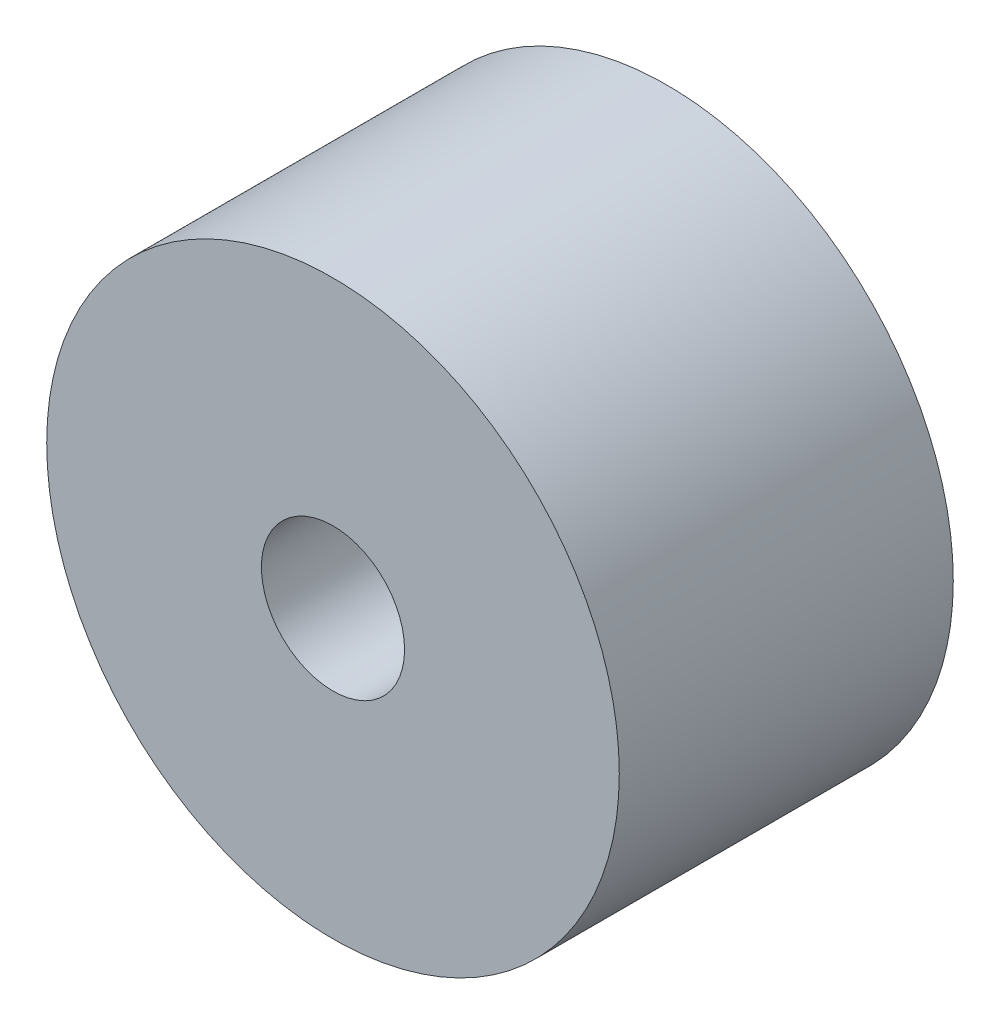
SolidWorks part; units mm, degrees
ref_plane "Plan de face" through (0, 0, 0) normal (0, 0, 1) x (1, 0, 0)
ref_plane "Plan de dessus" through (0, 0, 0) normal (0, 1, 0) x (1, 0, 0)
ref_plane "Plan de droite" through (0, 0, 0) normal (1, 0, 0) x (0, 0, -1)
sketch "Esquisse1" plane through (0, 0, 0) normal (0, 0, 1) x (1, 0, 0)
  arc A0 (2.9773, 0.3683) -> (2.9271, 0.6573) centre (0, 0) ccw
  arc A1 (2.1922, 2.048) -> (1.9817, 2.2523) centre (0, 0) ccw
  arc A2 (0.5698, 2.9454) -> (0.2794, 2.987) centre (0, 0) ccw
  arc A3 (-1.2703, 2.7178) -> (-1.5297, 2.5807) centre (0, 0) ccw
  arc A4 (-2.6252, 1.4521) -> (-2.7544, 1.1887) centre (0, 0) ccw
  arc A5 (-2.9773, -0.3683) -> (-2.9271, -0.6573) centre (0, 0) ccw
  arc A6 (-2.1922, -2.048) -> (-1.9817, -2.2523) centre (0, 0) ccw
  arc A7 (-0.5698, -2.9454) -> (-0.2794, -2.987) centre (0, 0) ccw
  arc A8 (1.2703, -2.7178) -> (1.5297, -2.5807) centre (0, 0) ccw
  arc A9 (2.6252, -1.4521) -> (2.7544, -1.1887) centre (0, 0) ccw
  arc A10 (1.8368, -0.3764) -> (1.8687, -0.154) centre (0, 0) ccw
  arc A11 (1.7073, 0.7751) -> (1.6023, 0.9738) centre (0, 0) ccw
  arc A12 (0.9256, 1.6306) -> (0.7239, 1.7296) centre (0, 0) ccw
  arc A13 (-0.2096, 1.8632) -> (-0.431, 1.8248) centre (0, 0) ccw
  arc A14 (-1.2648, 1.3842) -> (-1.4213, 1.2229) centre (0, 0) ccw
  arc A15 (-1.8368, 0.3764) -> (-1.8687, 0.154) centre (0, 0) ccw
  arc A16 (-1.7073, -0.7751) -> (-1.6023, -0.9738) centre (0, 0) ccw
  arc A17 (-0.9256, -1.6306) -> (-0.7239, -1.7296) centre (0, 0) ccw
  arc A18 (0.2096, -1.8632) -> (0.431, -1.8248) centre (0, 0) ccw
  arc A19 (1.2648, -1.3842) -> (1.4213, -1.2229) centre (0, 0) ccw
  circle A20 centre (0, 0) radius 0.75
  spline S0 degree 3 poles (2.349, 0) (2.3611, 0) (2.4126, 0.0085) (2.4945, 0.0326) (2.6584, 0.1065) (2.823, 0.2207) (2.9394, 0.3292) (2.9773, 0.3683) knots 0 0 0 0 0.036251 0.155621 0.255291 0.575255 0.744085 0.744085 0.744085 0.744085
  spline S1 degree 3 poles (2.2114, 0.7921) (2.2228, 0.7962) (2.2741, 0.8056) (2.3594, 0.8105) (2.5386, 0.7962) (2.7321, 0.7442) (2.8782, 0.6813) (2.9271, 0.6573) knots 0 0 0 0 0.036251 0.155621 0.255291 0.575255 0.744085 0.744085 0.744085 0.744085
  spline S2 degree 3 poles (1.9004, 1.3807) (1.9102, 1.3878) (1.9469, 1.4249) (1.9989, 1.4926) (2.0881, 1.6487) (2.1541, 1.8379) (2.1845, 1.9941) (2.1922, 2.048) knots 0 0 0 0 0.036251 0.155621 0.255291 0.575255 0.744085 0.744085 0.744085 0.744085
  spline S3 degree 3 poles (1.3235, 1.9407) (1.3303, 1.9507) (1.3663, 1.9885) (1.4324, 2.0425) (1.5858, 2.1363) (1.7728, 2.2079) (1.9281, 2.243) (1.9817, 2.2523) knots 0 0 0 0 0.036251 0.155621 0.255291 0.575255 0.744085 0.744085 0.744085 0.744085
  spline S4 degree 3 poles (0.7259, 2.234) (0.7296, 2.2455) (0.7375, 2.2971) (0.7398, 2.3825) (0.7202, 2.5612) (0.6625, 2.753) (0.5952, 2.8973) (0.5698, 2.9454) knots 0 0 0 0 0.036251 0.155621 0.255291 0.575255 0.744085 0.744085 0.744085 0.744085
  spline S5 degree 3 poles (-0.07, 2.348) (-0.0704, 2.36) (-0.0634, 2.4118) (-0.0417, 2.4943) (0.0272, 2.6604) (0.1365, 2.8283) (0.2415, 2.9479) (0.2794, 2.987) knots 0 0 0 0 0.036251 0.155621 0.255291 0.575255 0.744085 0.744085 0.744085 0.744085
  spline S6 degree 3 poles (-0.7259, 2.234) (-0.7296, 2.2455) (-0.7536, 2.2919) (-0.8019, 2.3623) (-0.9228, 2.4954) (-1.0823, 2.6166) (-1.2215, 2.6938) (-1.2703, 2.7178) knots 0 0 0 0 0.036251 0.155621 0.255291 0.575255 0.744085 0.744085 0.744085 0.744085
  spline S7 degree 3 poles (-1.4367, 1.8584) (-1.4441, 1.8679) (-1.4689, 1.9139) (-1.4999, 1.9934) (-1.5417, 2.1683) (-1.552, 2.3684) (-1.5374, 2.5268) (-1.5297, 2.5807) knots 0 0 0 0 0.036251 0.155621 0.255291 0.575255 0.744085 0.744085 0.744085 0.744085
  spline S8 degree 3 poles (-1.9004, 1.3807) (-1.9102, 1.3878) (-1.9568, 1.4112) (-2.0373, 1.4398) (-2.2133, 1.4764) (-2.4136, 1.4808) (-2.5715, 1.4614) (-2.6252, 1.4521) knots 0 0 0 0 0.036251 0.155621 0.255291 0.575255 0.744085 0.744085 0.744085 0.744085
  spline S9 degree 3 poles (-2.2547, 0.659) (-2.2663, 0.6624) (-2.3133, 0.6849) (-2.3852, 0.7311) (-2.5218, 0.848) (-2.6477, 1.0038) (-2.729, 1.1406) (-2.7544, 1.1887) knots 0 0 0 0 0.036251 0.155621 0.255291 0.575255 0.744085 0.744085 0.744085 0.744085
  spline S10 degree 3 poles (-2.349, 0) (-2.3611, 0) (-2.4126, -0.0085) (-2.4945, -0.0326) (-2.6584, -0.1065) (-2.823, -0.2207) (-2.9394, -0.3292) (-2.9773, -0.3683) knots 0 0 0 0 0.036251 0.155621 0.255291 0.575255 0.744085 0.744085 0.744085 0.744085
  spline S11 degree 3 poles (-2.2114, -0.7921) (-2.2228, -0.7962) (-2.2741, -0.8056) (-2.3594, -0.8105) (-2.5386, -0.7962) (-2.7321, -0.7442) (-2.8782, -0.6813) (-2.9271, -0.6573) knots 0 0 0 0 0.036251 0.155621 0.255291 0.575255 0.744085 0.744085 0.744085 0.744085
  spline S12 degree 3 poles (-1.9004, -1.3807) (-1.9102, -1.3878) (-1.9469, -1.4249) (-1.9989, -1.4926) (-2.0881, -1.6487) (-2.1541, -1.8379) (-2.1845, -1.9941) (-2.1922, -2.048) knots 0 0 0 0 0.036251 0.155621 0.255291 0.575255 0.744085 0.744085 0.744085 0.744085
  spline S13 degree 3 poles (-1.3235, -1.9407) (-1.3303, -1.9507) (-1.3663, -1.9885) (-1.4324, -2.0425) (-1.5858, -2.1363) (-1.7728, -2.2079) (-1.9281, -2.243) (-1.9817, -2.2523) knots 0 0 0 0 0.036251 0.155621 0.255291 0.575255 0.744085 0.744085 0.744085 0.744085
  spline S14 degree 3 poles (-0.7259, -2.234) (-0.7296, -2.2455) (-0.7375, -2.2971) (-0.7398, -2.3825) (-0.7202, -2.5612) (-0.6625, -2.753) (-0.5952, -2.8973) (-0.5698, -2.9454) knots 0 0 0 0 0.036251 0.155621 0.255291 0.575255 0.744085 0.744085 0.744085 0.744085
  spline S15 degree 3 poles (0.07, -2.348) (0.0704, -2.36) (0.0634, -2.4118) (0.0417, -2.4943) (-0.0272, -2.6604) (-0.1365, -2.8283) (-0.2415, -2.9479) (-0.2794, -2.987) knots 0 0 0 0 0.036251 0.155621 0.255291 0.575255 0.744085 0.744085 0.744085 0.744085
  spline S16 degree 3 poles (0.7259, -2.234) (0.7296, -2.2455) (0.7536, -2.2919) (0.8019, -2.3623) (0.9228, -2.4954) (1.0823, -2.6166) (1.2215, -2.6938) (1.2703, -2.7178) knots 0 0 0 0 0.036251 0.155621 0.255291 0.575255 0.744085 0.744085 0.744085 0.744085
  spline S17 degree 3 poles (1.4367, -1.8584) (1.4441, -1.8679) (1.4689, -1.9139) (1.4999, -1.9934) (1.5417, -2.1683) (1.552, -2.3684) (1.5374, -2.5268) (1.5297, -2.5807) knots 0 0 0 0 0.036251 0.155621 0.255291 0.575255 0.744085 0.744085 0.744085 0.744085
  spline S18 degree 3 poles (1.9004, -1.3807) (1.9102, -1.3878) (1.9568, -1.4112) (2.0373, -1.4398) (2.2133, -1.4764) (2.4136, -1.4808) (2.5715, -1.4614) (2.6252, -1.4521) knots 0 0 0 0 0.036251 0.155621 0.255291 0.575255 0.744085 0.744085 0.744085 0.744085
  spline S19 degree 3 poles (2.2547, -0.659) (2.2663, -0.6624) (2.3133, -0.6849) (2.3852, -0.7311) (2.5218, -0.848) (2.6477, -1.0038) (2.729, -1.1406) (2.7544, -1.1887) knots 0 0 0 0 0.036251 0.155621 0.255291 0.575255 0.744085 0.744085 0.744085 0.744085
  spline S20 degree 3 poles (2.349, 0) (2.2648, 0) (2.1034, 0.0291) (1.8817, -0.0633) (1.8687, -0.154) knots 0 0 0 0 0.252618 0.527509 0.527509 0.527509 0.527509
  spline S21 degree 3 poles (2.2547, -0.659) (2.1739, -0.6353) (2.0108, -0.618) (1.8238, -0.4671) (1.8368, -0.3764) knots 0 0 0 0 0.252618 0.527509 0.527509 0.527509 0.527509
  spline S22 degree 3 poles (1.9004, 1.3807) (1.8323, 1.3312) (1.6846, 1.2599) (1.5595, 1.0548) (1.6023, 0.9738) knots 0 0 0 0 0.252618 0.527509 0.527509 0.527509 0.527509
  spline S23 degree 3 poles (2.2114, 0.7921) (2.1321, 0.7637) (1.99, 0.682) (1.7501, 0.6941) (1.7073, 0.7751) knots 0 0 0 0 0.252618 0.527509 0.527509 0.527509 0.527509
  spline S24 degree 3 poles (0.7259, 2.234) (0.6999, 2.1539) (0.6223, 2.0095) (0.6416, 1.77) (0.7239, 1.7296) knots 0 0 0 0 0.252618 0.527509 0.527509 0.527509 0.527509
  spline S25 degree 3 poles (1.3235, 1.9407) (1.276, 1.8711) (1.2091, 1.7214) (1.0079, 1.5902) (0.9256, 1.6306) knots 0 0 0 0 0.252618 0.527509 0.527509 0.527509 0.527509
  spline S26 degree 3 poles (-0.7259, 2.234) (-0.6999, 2.1539) (-0.6776, 1.9915) (-0.5213, 1.8091) (-0.431, 1.8248) knots 0 0 0 0 0.252618 0.527509 0.527509 0.527509 0.527509
  spline S27 degree 3 poles (-0.07, 2.348) (-0.0675, 2.2638) (-0.0336, 2.1034) (-0.1193, 1.8789) (-0.2096, 1.8632) knots 0 0 0 0 0.252618 0.527509 0.527509 0.527509 0.527509
  spline S28 degree 3 poles (-1.9004, 1.3807) (-1.8323, 1.3312) (-1.7188, 1.2128) (-1.4851, 1.1572) (-1.4213, 1.2229) knots 0 0 0 0 0.252618 0.527509 0.527509 0.527509 0.527509
  spline S29 degree 3 poles (-1.4367, 1.8584) (-1.3852, 1.7918) (-1.2635, 1.6819) (-1.2009, 1.4499) (-1.2648, 1.3842) knots 0 0 0 0 0.252618 0.527509 0.527509 0.527509 0.527509
  spline S30 degree 3 poles (-2.349, 0) (-2.2648, 0) (-2.1034, -0.0291) (-1.8817, 0.0633) (-1.8687, 0.154) knots 0 0 0 0 0.252618 0.527509 0.527509 0.527509 0.527509
  spline S31 degree 3 poles (-2.2547, 0.659) (-2.1739, 0.6353) (-2.0108, 0.618) (-1.8238, 0.4671) (-1.8368, 0.3764) knots 0 0 0 0 0.252618 0.527509 0.527509 0.527509 0.527509
  spline S32 degree 3 poles (-1.9004, -1.3807) (-1.8323, -1.3312) (-1.6846, -1.2599) (-1.5595, -1.0548) (-1.6023, -0.9738) knots 0 0 0 0 0.252618 0.527509 0.527509 0.527509 0.527509
  spline S33 degree 3 poles (-2.2114, -0.7921) (-2.1321, -0.7637) (-1.99, -0.682) (-1.7501, -0.6941) (-1.7073, -0.7751) knots 0 0 0 0 0.252618 0.527509 0.527509 0.527509 0.527509
  spline S34 degree 3 poles (-0.7259, -2.234) (-0.6999, -2.1539) (-0.6223, -2.0095) (-0.6416, -1.77) (-0.7239, -1.7296) knots 0 0 0 0 0.252618 0.527509 0.527509 0.527509 0.527509
  spline S35 degree 3 poles (-1.3235, -1.9407) (-1.276, -1.8711) (-1.2091, -1.7214) (-1.0079, -1.5902) (-0.9256, -1.6306) knots 0 0 0 0 0.252618 0.527509 0.527509 0.527509 0.527509
  spline S36 degree 3 poles (0.7259, -2.234) (0.6999, -2.1539) (0.6776, -1.9915) (0.5213, -1.8091) (0.431, -1.8248) knots 0 0 0 0 0.252618 0.527509 0.527509 0.527509 0.527509
  spline S37 degree 3 poles (0.07, -2.348) (0.0675, -2.2638) (0.0336, -2.1034) (0.1193, -1.8789) (0.2096, -1.8632) knots 0 0 0 0 0.252618 0.527509 0.527509 0.527509 0.527509
  spline S38 degree 3 poles (1.9004, -1.3807) (1.8323, -1.3312) (1.7188, -1.2128) (1.4851, -1.1572) (1.4213, -1.2229) knots 0 0 0 0 0.252618 0.527509 0.527509 0.527509 0.527509
  spline S39 degree 3 poles (1.4367, -1.8584) (1.3852, -1.7918) (1.2635, -1.6819) (1.2009, -1.4499) (1.2648, -1.3842) knots 0 0 0 0 0.252618 0.527509 0.527509 0.527509 0.527509
  dimension "D1" = 1.5
extrude "Boss.-Extru.1" add sketch "Esquisse1" along normal blind 3.5
sketch "Esquisse2" plane through (0, 0, 0) normal (0, 0, -1) x (-1, 0, 0)
  circle A0 centre (0, 0) radius 3
  circle A1 centre (0, 0) radius 0.75 construction
  circle A2 centre (0, 0) radius 0.75
extrude "Boss.-Extru.2" add sketch "Esquisse2" against normal up to surface (3.5 mm away) up to face at (0, 0, 3.5)
